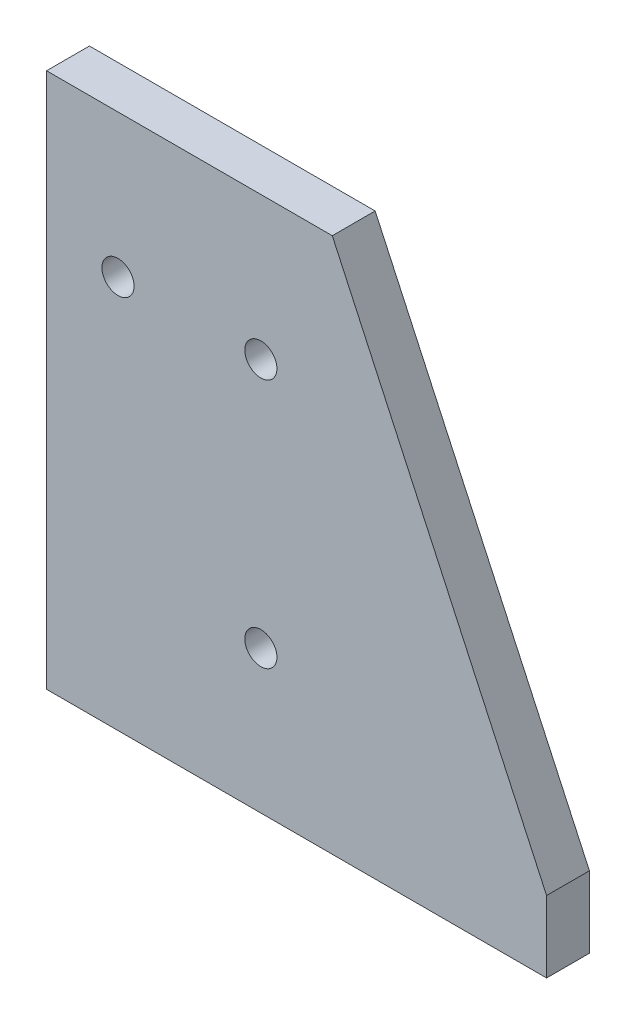
SolidWorks part; units mm, degrees
material "6061 合金"
ref_plane "前视基准面" through (0, 0, 0) normal (0, 0, 1) x (1, 0, 0)
ref_plane "上视基准面" through (0, 0, 0) normal (0, 1, 0) x (1, 0, 0)
ref_plane "右视基准面" through (0, 0, 0) normal (1, 0, 0) x (0, 0, -1)
other "Configuration Table"
sketch "Sketch1" plane through (0, 0, 0) normal (0, 0, 1) x (1, 0, 0)
  line L0 (0, 0) -> (140, 0)
  line L1 (140, 0) -> (140, 20)
  line L2 (140, 20) -> (80, 150)
  line L3 (80, 150) -> (0, 150)
  line L4 (0, 150) -> (0, 0)
extrude "Boss-Extrude1" add sketch "Sketch1" along normal blind 12
sketch "Sketch2" plane through (0, 0, 0) normal (0, 0, 1) x (1, 0, 0)
  circle A0 centre (20, 110) radius 4.5
  circle A1 centre (60, 110) radius 4.5
  circle A2 centre (60, 40) radius 4.5
extrude "Cut-Extrude1" cut sketch "Sketch2" against normal through all and the other way through all
sketch "Sketch3" plane through (0, 0, 0) normal (0, 1, 0) x (1, 0, 0)
  circle A0 centre (100, -6) radius 2.5
  circle A1 centre (125, -6) radius 2.5
extrude "Cut-Extrude3" cut sketch "Sketch3" along normal blind 15
